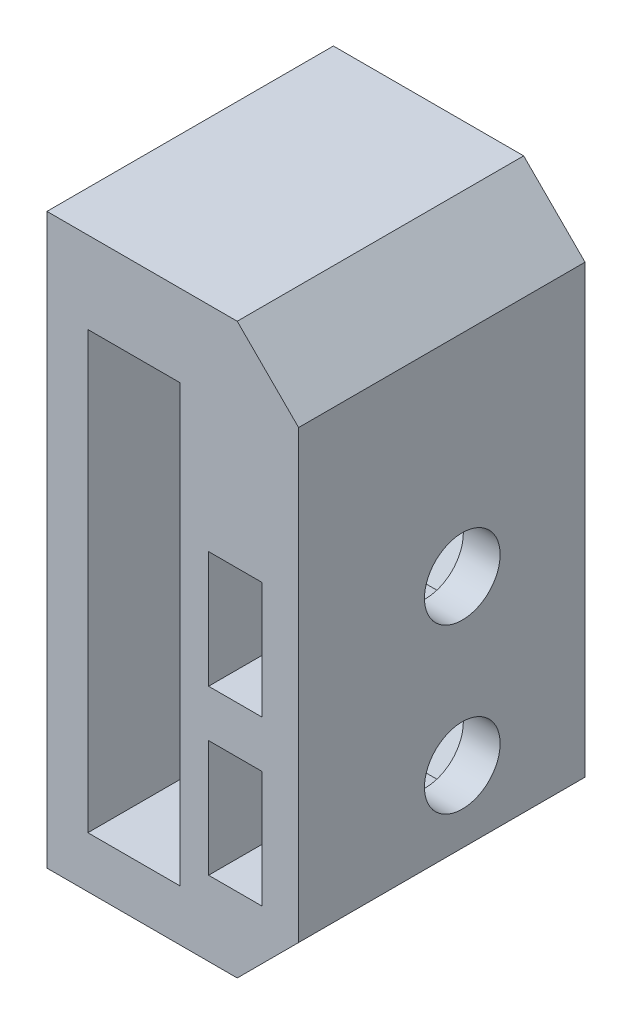
SolidWorks part; units mm, degrees
ref_plane "Front Plane" through (0, 0, 0) normal (1, 0, 0) x (0, 1, 0)
ref_plane "Top Plane" through (0, 0, 0) normal (0, 0, 1) x (0, 1, 0)
ref_plane "Right Plane" through (0, 0, 0) normal (0, 1, 0) x (-1, 0, 0)
sketch "Sketch1" plane through (0, 0, 0) normal (1, 0, 0) x (0, 1, 0)
  line L0 (4, 3.5) -> (12, 3.5) construction
  line L1 (0, 0) -> (21.3, 0)
  line L2 (0, 0) -> (0, 9)
  line L3 (0, 9) -> (21.3, 9)
  line L4 (21.3, 0) -> (21.3, 9)
  circle A0 centre (4, 3.5) radius 1.75 construction
  circle A1 centre (12, 3.5) radius 1.75 construction
  dimension "D3" = 3.5
  dimension "D4" = 3.5
  dimension "D1" = 21.3
  dimension "D2" = 9
  dimension "D5" = 4
  dimension "D6" = 3.5
  dimension "D7" = 8
extrude "Extrude-Thin1" add sketch "Sketch1" along normal blind 4.5 thin
sketch "Sketch2" plane through (4.5, 0, 0) normal (1, 0, 0) x (0, 1, 0)
  line L1 (-2.5, 11.5) -> (23.8, 11.5)
  line L2 (-2.5, 11.5) -> (-2.5, -2.5)
  line L3 (-2.5, -2.5) -> (23.8, -2.5)
  line L4 (23.8, 11.5) -> (23.8, -2.5)
extrude "Boss-Extrude1" add sketch "Sketch2" along normal blind 5.8
sketch "Sketch3" plane through (0, 0, 0) normal (-1, 0, 0) x (0, -1, 0)
  line L1 (-23.8, 11.5) -> (2.5, 11.5)
  line L2 (-23.8, 11.5) -> (-23.8, -2.5)
  line L3 (-23.8, -2.5) -> (2.5, -2.5)
  line L4 (2.5, 11.5) -> (2.5, -2.5)
extrude "Boss-Extrude2" add sketch "Sketch3" along normal blind 2
sketch "Sketch4" plane through (0, 0, 9) normal (0, 0, -1) x (1, 0, 0)
  line L1 (0, 0) -> (4.5, 0)
  line L2 (0, 0) -> (0, -21.3)
  line L3 (0, -21.3) -> (4.5, -21.3)
  line L4 (4.5, 0) -> (4.5, -21.3)
extrude "Cut-Extrude1" cut sketch "Sketch4" against normal blind 18
sketch "Sketch7" plane through (4.5, 0, 0) normal (-1, 0, 0) x (0, -1, 0)
  line L0 (-14.85, 6.2797) -> (-14.85, 11.5)
  line L1 (-14.85, 1.8546) -> (-12, 0.2091)
  line L2 (-12, 0.2091) -> (-9.15, 1.8546)
  line L3 (-9.15, 1.8546) -> (-9.15, 6.6913)
  line L6 (-14.85, 6.2797) -> (-14.85, 1.8546)
  line L7 (-6.85, 1.8546) -> (-4, 0.2091)
  line L8 (-4, 0.2091) -> (-1.15, 1.8546)
  line L9 (-1.15, 1.8546) -> (-1.15, 5.0989)
  line L12 (-6.85, 5.0267) -> (-6.85, 1.8546)
  line L14 (-14.85, 11.5) -> (-9.15, 11.5)
  line L15 (-21.3, 11.5) -> (0, 11.5) construction
  line L16 (-9.15, 11.5) -> (-9.15, 6.6913)
  line L17 (-6.85, 5.0267) -> (-6.85, 11.5)
  line L18 (-6.85, 11.5) -> (-1.15, 11.5)
  line L19 (-1.15, 11.5) -> (-1.15, 5.0989)
  line L21 (-13.425, 5.9682) -> (-14.825, 5.1599) [skipped]
  line L22 (-9.2528, 5.2048) -> (-10.6528, 6.0131) [skipped]
  line L23 (-4.1028, 6.7315) -> (-5.5028, 5.9232) [skipped]
  line L24 (-1.2528, 5.2048) -> (-2.6528, 6.0131) [skipped]
  circle A0 centre (-12, 3.5) radius 2.85 construction
  circle A1 centre (-4, 3.5) radius 2.85 construction
  dimension "D1" = 5.7
  dimension "D2" = 5.7
extrude "Cut-Extrude4" cut sketch "Sketch7" against normal blind 4
sketch "Sketch8" plane through (4.5, 0, 0) normal (-1, 0, 0) x (0, -1, 0)
  line L1 (-21.3, 11.5) -> (0, 11.5)
  line L2 (-21.3, 11.5) -> (-21.3, 0)
  line L3 (-21.3, 0) -> (0, 0)
  line L4 (0, 11.5) -> (0, 0)
extrude "Boss-Extrude3" add sketch "Sketch8" against normal blind 1.4
sketch "Sketch5" plane through (10.3, 0, 0) normal (1, 0, 0) x (0, 1, 0)
  circle A0 centre (4, 3.5) radius 1.85
  circle A1 centre (12, 3.5) radius 1.85
  dimension "D1" = 3.7
  dimension "D2" = 3.7
extrude "Cut-Extrude2" cut sketch "Sketch5" against normal blind 10
sketch "Sketch9" plane through (0, 23.8, 0) normal (0, 1, 0) x (-1, 0, 0)
  line L4 (-10.3, -2.5) -> (2, -2.5)
  line L5 (2, -2.5) -> (2, 11.5)
  line L6 (2, 11.5) -> (-10.3, 11.5)
  line L7 (-10.3, 11.5) -> (-10.3, -2.5)
  line L8 (-10.3, -2.5) -> (2, -2.5)
  line L9 (2, -2.5) -> (2, 11.5)
  line L10 (2, 11.5) -> (-10.3, 11.5)
  line L11 (-10.3, 11.5) -> (-10.3, -2.5)
  dimension "D1" = 0
extrude "Boss-Extrude4" add sketch "Sketch9" along normal blind 1.5
chamfer "Chamfer1" distance 3 angle 45 2 edges at (10.3, -2.5, 4.5) (10.3, 25.3, 4.5)
